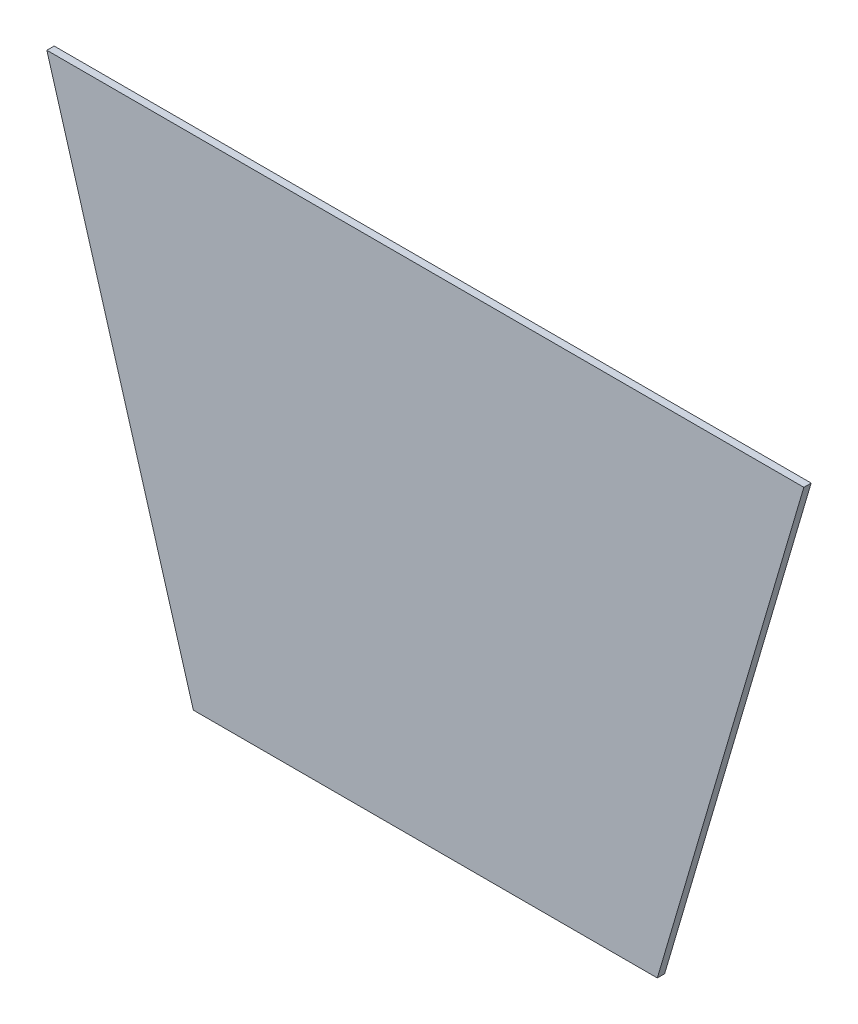
SolidWorks part; units mm, degrees
material "PVC 0.007 Plasticized"
ref_plane "Front Plane" through (0, 0, 0) normal (0, 0, 1) x (1, 0, 0)
ref_plane "Top Plane" through (0, 0, 0) normal (0, 1, 0) x (1, 0, 0)
ref_plane "Right Plane" through (0, 0, 0) normal (1, 0, 0) x (0, 0, -1)
sketch "Sketch1" plane through (0, 0, 0) normal (0, 0, 1) x (1, 0, 0)
  line L5 (-164.0205, 0) -> (164.0205, 0)
  line L6 (-100.5205, -215.9) -> (100.5205, -215.9)
  line L10 (-164.0205, 0) -> (-100.5205, -215.9)
  line L11 (164.0205, 0) -> (100.5205, -215.9)
  point P0 (0, 0)
  point P6 (0, -107.95)
  point P7 (-55.4265, 104.2984)
  point P8 (0, 0)
  dimension "D1" = 328.041
  dimension "D2" = 201.041
  dimension "D3" = 215.9
  dimension "D4" = 63.5
extrude "Boss-Extrude1" add sketch "Sketch1" against normal blind 3.175
